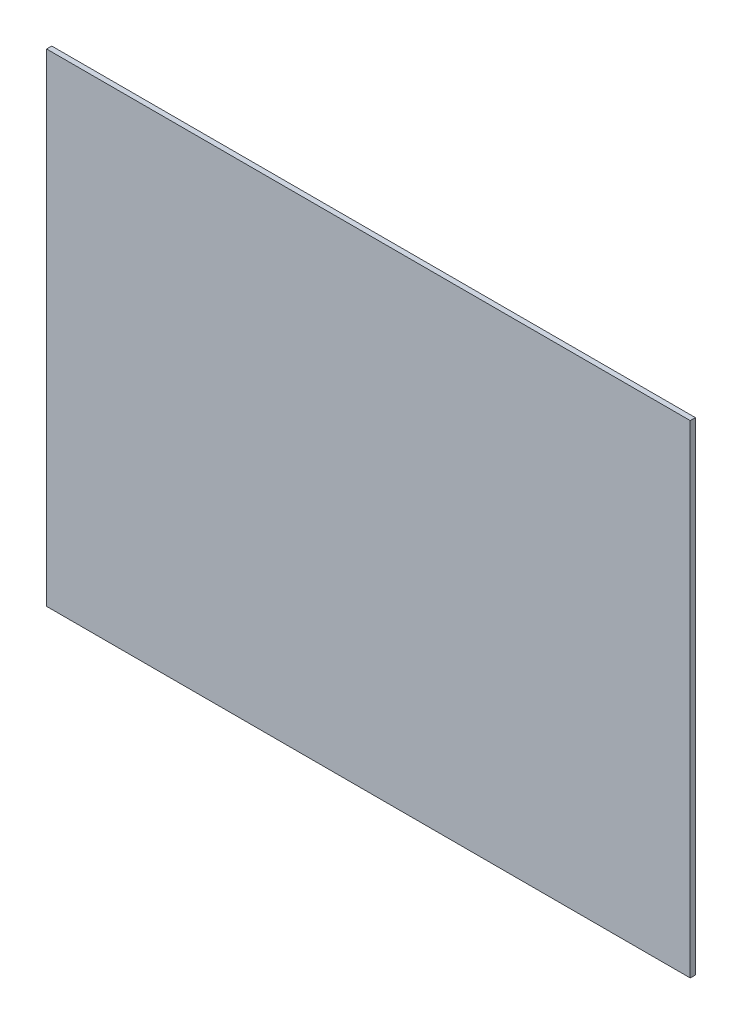
SolidWorks part; units mm, degrees
ref_plane "Ebene vorne" through (0, 0, 0) normal (0, 0, 1) x (1, 0, 0)
ref_plane "Ebene oben" through (0, 0, 0) normal (0, 1, 0) x (1, 0, 0)
ref_plane "Ebene rechts" through (0, 0, 0) normal (1, 0, 0) x (0, 0, -1)
sketch "Skizze2" plane through (0, 0, 0) normal (0, 0, 1) x (1, 0, 0)
  line L1 (-1000, -750) -> (1000, -750)
  line L2 (-1000, -750) -> (-1000, 750)
  line L3 (-1000, 750) -> (1000, 750)
  line L4 (1000, -750) -> (1000, 750)
  line L5 (-1000, -750) -> (1000, 750) construction
  line L6 (-1000, 750) -> (1000, -750) construction
  point P0 (0, 0)
  dimension "D1" = 2000
  dimension "D2" = 1500
extrude "Aufsatz-Linear austragen1" add sketch "Skizze2" along normal blind 16
